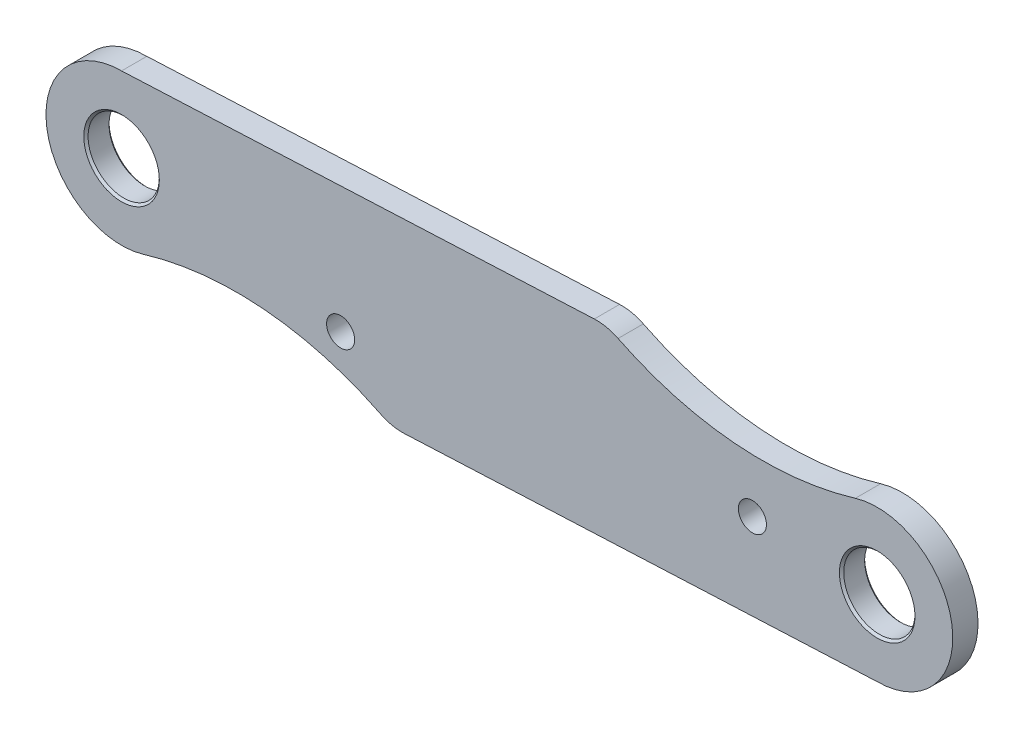
SolidWorks part; units mm, degrees
material "AISI 1020"
ref_plane "Alzado" through (0, 0, 0) normal (0, 0, 1) x (1, 0, 0)
ref_plane "Planta" through (0, 0, 0) normal (0, 1, 0) x (1, 0, 0)
ref_plane "Vista lateral" through (0, 0, 0) normal (1, 0, 0) x (0, 0, -1)
sketch "Croquis1" plane through (0, 0, 0) normal (0, 0, 1) x (1, 0, 0)
  line L0 (0, 0) -> (0, 77.5204) construction
  line L1 (-197.5, 25) -> (197.5, 25)
  line L3 (-197.5, -25) -> (197.5, -25)
  line L5 (-197.5, 25) -> (197.5, -25) construction
  line L6 (-197.5, -25) -> (197.5, 25) construction
  line L7 (-197.5, 0) -> (-193.2286, 0) construction
  circle A0 centre (-175, 0) radius 16.5
  circle A1 centre (175, 0) radius 16.5
  arc A2 (-197.5, -25) -> (-197.5, 25) centre (-144.7141, 0) cw
  arc A3 (197.5, -25) -> (197.5, 25) centre (144.7141, 0) ccw
  circle A4 centre (75, 0) radius 6.375 construction
  circle A5 centre (-75, 0) radius 6.375 construction
  point P0 (0, 0)
  dimension "D2" = 33
  dimension "D4" = 350
  dimension "D5" = 175
  dimension "D6" = 58.4068
  dimension "D7" = 12.75
  dimension "D1" = 50
  dimension "D3" = 395
  dimension "D8" = 75
extrude "Saliente-Extruir1" add sketch "Croquis1" along normal blind 11.7
sketch "Croquis9" plane through (0, 0, 11.7) normal (0, 0, 1) x (1, 0, 0)
  line L0 (-175, 0) -> (45, 22.5) construction
  line L1 (45, 22.5) -> (-45, -22.5) construction
  line L2 (-45, -22.5) -> (175, 0) construction
  line L3 (-175, 0) -> (175, 0) construction
  line L4 (0, 0) -> (0, 120.8403) construction
  line L5 (-175, 35) -> (43.9759, 44.9767)
  line L6 (175, -35) -> (-43.9759, -44.9767)
  circle A0 centre (-175, 0) radius 16.5
  circle A1 centre (-175, 0) radius 16.5 construction
  circle A2 centre (175, 0) radius 16.5
  circle A3 centre (-175, 0) radius 35
  circle A4 centre (175, 0) radius 35
  circle A5 centre (45, 22.5) radius 22.5
  circle A6 centre (-45, -22.5) radius 22.5
  arc A7 (-164.8817, -33.5055) -> (-54.9805, -42.6653) centre (-121.5174, -177.1006) cw
  arc A8 (54.9805, 42.6653) -> (164.8817, 33.5055) centre (121.5174, 177.1006) ccw
  circle A12 centre (-175, 0) radius 16.5 construction
  circle M1 centre (-175, 0) radius 16.5
  arc M2 (197.5, -25) -> (197.5, 25) centre (144.7141, 0) ccw
  line M3 (197.5, 25) -> (-197.5, 25)
  arc M4 (-197.5, 25) -> (-197.5, -25) centre (-144.7141, 0) ccw
  line M5 (-197.5, -25) -> (197.5, -25)
  circle M6 centre (175, 0) radius 16.5
extrude "Saliente-Extruir6" add sketch "Croquis9" against normal up to surface (11.7 mm away) contours A3 M5 M3 M4 M1 | A3 M3 M5 M4 | A5 L5 A3 M3 | A6 A4 A5 A3 M5 M3 | A3 A7 A6 M5 | A6 M5 | A6 M5 | A5 M3 | A5 M3 | A8 A5 A4 M3 | A6 L6 A4 M5 | A4 M5 M3 M2 | A4 M3 M5 M2 M6 up to face at (0, 0, 0)
sketch "Croquis8" plane through (0, 0, 11.7) normal (0, 0, 1) x (1, 0, 0)
  line L0 (-175, 0) -> (45, 22.5) construction
  line L1 (45, 22.5) -> (-45, -22.5) construction
  line L2 (-45, -22.5) -> (175, 0) construction
  line L3 (-175, 0) -> (175, 0) construction
  line L4 (0, 0) -> (0, 120.8403) construction
  line L5 (-175, 35) -> (43.9759, 44.9767)
  line L6 (175, -35) -> (-43.9759, -44.9767)
  circle A0 centre (-175, 0) radius 16.5
  circle A1 centre (-175, 0) radius 16.5 construction
  circle A2 centre (175, 0) radius 16.5
  circle A3 centre (-175, 0) radius 35
  circle A4 centre (175, 0) radius 35
  circle A5 centre (45, 22.5) radius 22.5
  circle A6 centre (-45, -22.5) radius 22.5
  arc A7 (-164.8817, -33.5055) -> (-54.9805, -42.6653) centre (-121.5174, -177.1006) cw
  arc A8 (54.9805, 42.6653) -> (164.8817, 33.5055) centre (121.5174, 177.1006) ccw
  circle A9 centre (-175, 0) radius 16.5 construction
  dimension "D1" = 33
  dimension "D3" = 33
  dimension "D5" = 220
  dimension "D9" = 70
  dimension "D10" = 70
  dimension "D12" = 150
  dimension "D6" = 220
  dimension "D7" = 22.5
  dimension "D8" = 22.5
extrude "Saliente-Extruir5" add sketch "Croquis8" against normal up to surface (11.7 mm away) up to face at (-158.5, 0, 0)
sketch "Croquis2" plane through (0, 0, 11.7) normal (0, 0, 1) x (1, 0, 0)
  line L0 (-175, 0) -> (-144.561, 0) construction
  circle A0 centre (5, 0) radius 6.5
  circle A1 centre (-175, 0) radius 16.5 construction
  dimension "D1" = 180
  dimension "D2" = 13
extrude "Cortar-Extruir1" [suppressed] cut sketch "Croquis2" against normal through all
sketch "Croquis17" plane through (0, 0, 11.7) normal (0, 0, 1) x (1, 0, 0)
  circle A0 centre (-79.46, 20) radius 6
  circle A1 centre (-175, 0) radius 16.5 construction
  circle A2 centre (114.15, -1.2255) radius 6
  dimension "D1" = 95.54
  dimension "D2" = 20
  dimension "D3" = 12
  dimension "D4" = 289.15
  dimension "D5" = 194.77
extrude "Cortar-Extruir5" [suppressed] cut sketch "Croquis17" against normal through all
sketch "Croquis18" plane through (0, 0, 11.7) normal (0, 0, 1) x (1, 0, 0)
  circle A2 centre (113.61, -16.2255) radius 6
  circle A3 centre (-80, 5) radius 6
  circle A5 centre (-175, 0) radius 16.5 construction
  dimension "D1" = 194.77
  dimension "D2" = 12
  dimension "D3" = 12
  dimension "D4" = 21.2255
  dimension "D5" = 5
  dimension "D6" = 95
extrude "Cortar-Extruir6" [suppressed] cut sketch "Croquis18" against normal through all both and the other way through all
chamfer "Chaflán1" distance 1 angle 45 4 edges at (-158.5, 0, 0) (191.5, 0, 0) (191.5, 0, 11.7) (-158.5, 0, 11.7)
sketch "Croquis19" plane through (0, 0, 0) normal (0, 0, -1) x (-1, 0, 0)
  line L0 (43.9759, -44.9767) -> (-175, -35) construction
  line L1 (43.9759, -44.9767) -> (-175, -35) construction
  line L6 (73.5346, -18.9015) -> (173.9304, -23.4756) construction
  line L7 (175, 0) -> (173.9304, -23.4756) construction
  line L8 (-117.2005, 2.3014) -> (255.3479, -14.6721) construction
  circle A4 centre (175, 0) radius 16.5 construction
  circle A6 centre (175, 0) radius 16.5 construction
  circle A7 centre (73.5346, -18.9015) radius 6.5
  circle A8 centre (-117.2005, 2.3014) radius 6.5
  dimension "D7" = 13
  dimension "D10" = 13
  dimension "D12" = 191.91
  dimension "D8" = 100.5
  dimension "D9" = 23.5
  dimension "D11" = 11
extrude "Cortar-Extruir7" cut sketch "Croquis19" against normal up to next
